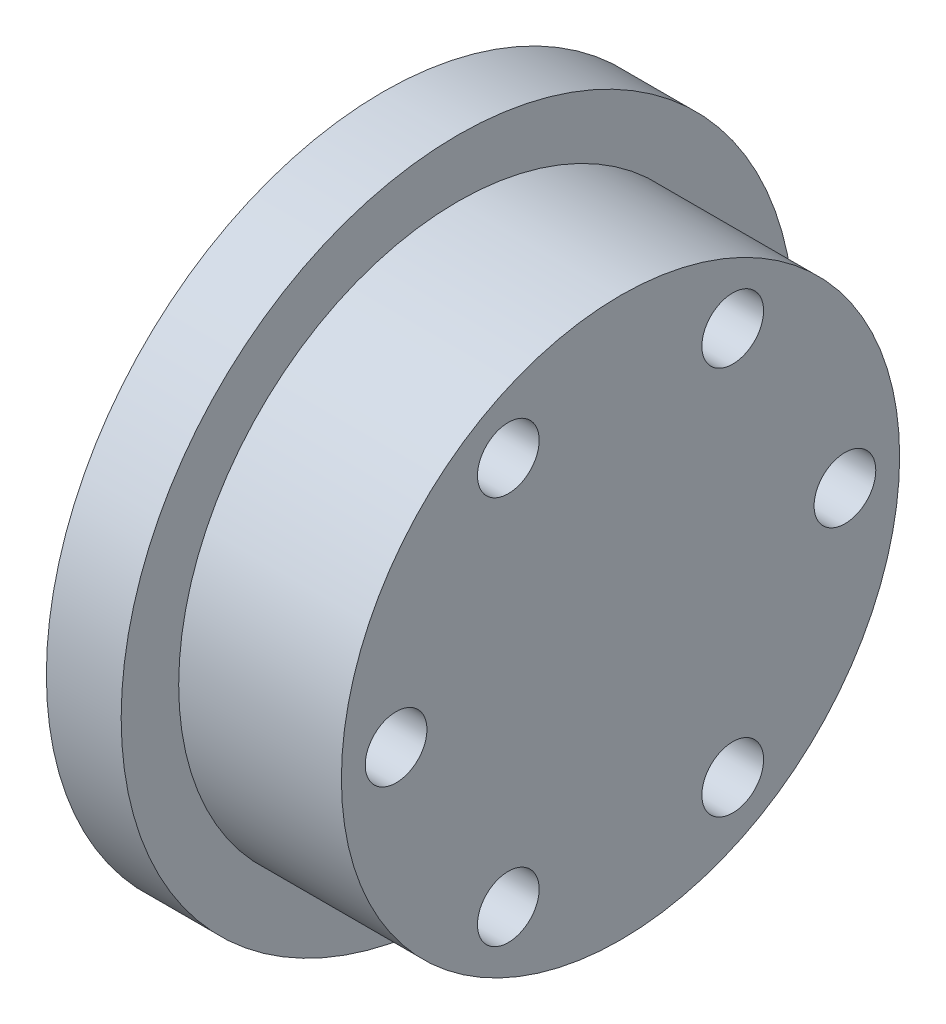
SolidWorks part; units mm, degrees
ref_plane "Front Plane" through (0, 0, 0) normal (1, 0, 0) x (0, 1, 0)
ref_plane "Top Plane" through (0, 0, 0) normal (0, 0, 1) x (0, 1, 0)
ref_plane "Right Plane" through (0, 0, 0) normal (0, 1, 0) x (-1, 0, 0)
sketch "Sketch1" plane through (0, 0, 0) normal (1, 0, 0) x (0, 1, 0)
  circle A0 centre (0, 0) radius 18
  dimension "D1" = 36
extrude "Boss-Extrude1" add sketch "Sketch1" along normal blind 4 contours A0
sketch "Sketch2" plane through (4, 0, 0) normal (1, 0, 0) x (0, 1, 0)
  circle A0 centre (0, 0) radius 14.925
  dimension "D1" = 29.85
extrude "Boss-Extrude2" add sketch "Sketch2" along normal blind 8.7
sketch "Sketch3" plane through (12.7, 0, 0) normal (1, 0, 0) x (0, 1, 0)
  circle A0 centre (0, 12) radius 1.65
  circle A1 centre (10.3923, 6) radius 1.65
  circle A2 centre (10.3923, -6) radius 1.65
  circle A3 centre (0, -12) radius 1.65
  circle A4 centre (-10.3923, -6) radius 1.65
  circle A5 centre (-10.3923, 6) radius 1.65
  point P4 (-11.1467, 6.9396)
  point P5 (0, 0)
  point P15 (0, 0)
  dimension "D1" = 3.3
  dimension "D2" = 12
  dimension "D3" = 6
extrude "Cut-Extrude1" cut sketch "Sketch3" against normal through all
